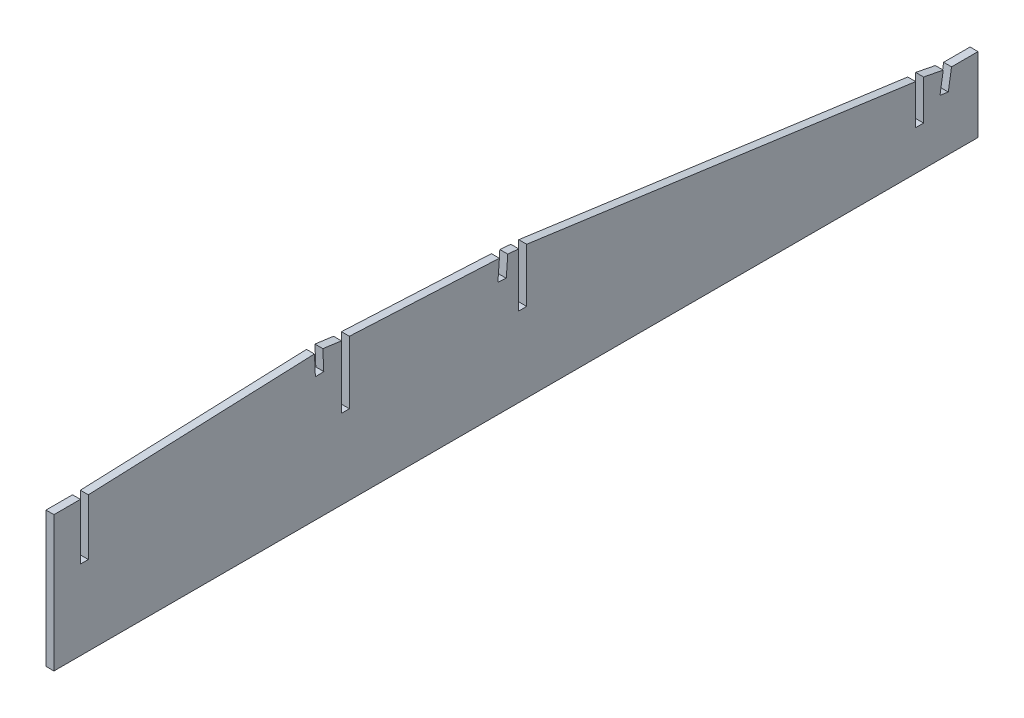
SolidWorks part; units mm, degrees
ref_plane "Front Plane" through (0, 0, 0) normal (0, 0, 1) x (1, 0, 0)
ref_plane "Top Plane" through (0, 0, 0) normal (0, 1, 0) x (1, 0, 0)
ref_plane "Right Plane" through (0, 0, 0) normal (1, 0, 0) x (0, 0, -1)
ref_plane "Plane1" through (341.221, 0, 0) normal (1, 0, 0) x (0, 0, -1)
sketch "Sketch1" plane through (341.221, 0, 0) normal (1, 0, 0) x (0, 0, -1)
  line L0 (257.343, 67.623) -> (257.343, 46.4388)
  line L1 (257.343, 16.4388) -> (257.343, 46.4388)
  line L2 (254.343, 67.623) -> (254.343, 46.4388)
  line L3 (254.343, 16.4388) -> (254.343, 46.4388)
  line L4 (257.343, 67.623) -> (254.343, 67.623)
  line L5 (254.343, 46.4388) -> (257.343, 46.4388)
  line L6 (254.343, 16.4388) -> (257.343, 16.4388)
  line L7 (254.343, 67.623) -> (244.343, 67.623)
  line L8 (254.343, 46.4388) -> (257.343, 46.4388)
  line L10 (244.343, 67.623) -> (244.343, 16.4388)
  line L11 (254.343, 67.623) -> (254.343, 46.4388)
  line L12 (244.343, 16.4388) -> (593.5558, 16.4388)
  line L13 (257.343, 67.623) -> (257.343, 46.4388)
  line L14 (573, 16.4388) -> (573, 31.4436)
  line L15 (573, 31.4436) -> (573, 46.5285)
  line L16 (570, 16.4388) -> (570, 31.4436)
  line L17 (570, 31.4436) -> (570, 46.5285)
  line L18 (570, 31.4436) -> (573, 31.4436)
  line L19 (570, 16.4388) -> (573, 16.4388)
  line L20 (573, 46.5285) -> (570, 46.5285)
  line L22 (593.5558, 16.4388) -> (593.5558, 44.5676)
  line L23 (570, 31.4436) -> (573, 31.4436)
  line L24 (570, 31.4436) -> (570, 46.5285)
  line L25 (593.5558, 44.5676) -> (583.5558, 44.5676)
  line L26 (573, 31.4436) -> (573, 46.5285)
  line L27 (580.4209, 45.0708) -> (573, 46.5285)
  line L28 (420, 16.4388) -> (420, 46.4388)
  line L29 (420, 46.4388) -> (420, 66.7823)
  line L30 (423, 16.4388) -> (423, 46.4388)
  line L31 (423, 46.4388) -> (423, 66.7823)
  line L32 (420, 66.7823) -> (423, 66.7823)
  line L33 (423, 16.4388) -> (420, 16.4388)
  line L34 (423, 46.4388) -> (420, 46.4388)
  line L35 (423, 46.4388) -> (420, 46.4388)
  line L36 (570, 46.5285) -> (423, 66.7823)
  line L38 (423, 46.4388) -> (423, 66.7823)
  line L39 (420, 66.7823) -> (415.8452, 67.1343)
  line L40 (420, 46.4388) -> (420, 66.7823)
  line L41 (412.6789, 67.3695) -> (356, 70.1746)
  line L42 (353, 70.1746) -> (353, 46.4388)
  line L43 (353, 16.4388) -> (353, 46.4388)
  line L44 (356, 70.1746) -> (356, 46.4388)
  line L45 (356, 16.4388) -> (356, 46.4388)
  line L46 (353, 70.1746) -> (356, 70.1746)
  line L47 (356, 16.4388) -> (353, 16.4388)
  line L48 (356, 46.4388) -> (353, 46.4388)
  line L49 (356, 46.4388) -> (353, 46.4388)
  line L50 (353, 70.1746) -> (345.9606, 71.1362)
  line L52 (342.789, 70.9886) -> (257.343, 67.623)
  line L53 (356, 70.1746) -> (356, 46.4388)
  line L54 (254.343, 16.4388) -> (257.343, 16.4388) construction
  line L55 (353, 70.1746) -> (353, 46.4388)
  line L56 (583.5558, 44.5676) -> (582.3316, 36.9403)
  line L57 (580.4209, 45.0708) -> (579.1968, 37.4435)
  line L58 (579.1968, 37.4435) -> (582.3316, 36.9403)
  line L59 (583.5558, 44.5676) -> (580.4209, 45.0708)
  line L61 (579.1968, 37.4435) -> (582.3316, 36.9403)
  line L62 (580.4209, 45.0708) -> (579.1968, 37.4435)
  line L63 (583.5558, 44.5676) -> (582.3316, 36.9403)
  line L64 (412.1133, 59.7545) -> (412.6789, 67.3695)
  line L65 (415.2796, 59.5193) -> (415.8452, 67.1343)
  line L66 (415.2796, 59.5193) -> (412.1133, 59.7545)
  line L67 (412.6789, 67.3695) -> (415.8452, 67.1343)
  line L69 (415.2796, 59.5193) -> (412.1133, 59.7545)
  line L70 (415.2796, 59.5193) -> (415.8452, 67.1343)
  line L71 (412.1133, 59.7545) -> (412.6789, 67.3695)
  line L72 (343.146, 63.3157) -> (342.789, 70.9886)
  line L73 (346.3176, 63.4633) -> (345.9606, 71.1362)
  line L74 (345.9606, 71.1362) -> (342.789, 70.9886)
  line L75 (343.146, 63.3157) -> (346.3176, 63.4633)
  line L76 (343.146, 63.3157) -> (346.3176, 63.4633)
  line L78 (346.3176, 63.4633) -> (345.9606, 71.1362)
  line L79 (343.146, 63.3157) -> (342.789, 70.9886)
  dimension "D1" = 10
  dimension "D2" = 10
extrude "Boss-Extrude1" add sketch "Sketch1" along normal blind 3
